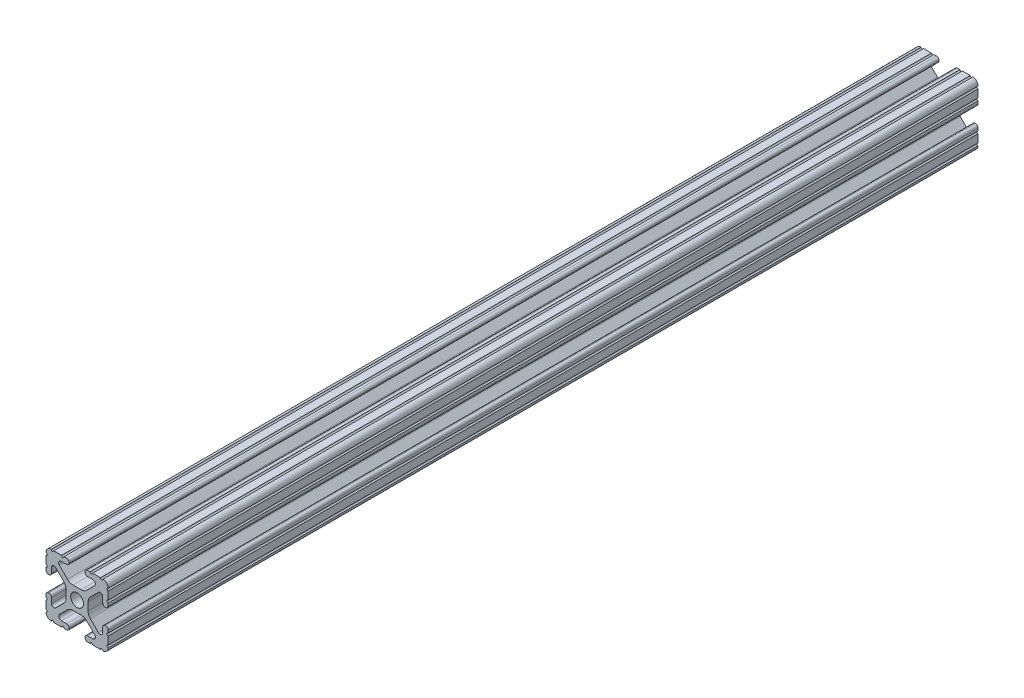
SolidWorks part; units mm, degrees
ref_plane "Front Plane" through (0, 0, 0) normal (0, 0, 1) x (1, 0, 0)
ref_plane "Top Plane" through (0, 0, 0) normal (0, 1, 0) x (1, 0, 0)
ref_plane "Right Plane" through (0, 0, 0) normal (1, 0, 0) x (0, 0, -1)
sketch "Sketch1" plane through (0, 0, 0) normal (0, 0, 1) x (1, 0, 0)
  line L88 (-7.1797, -8.6452) -> (-3.9523, -5.4237)
  line L89 (-1.7093, -4.4958) -> (1.7093, -4.4958)
  line L90 (3.9523, -5.4237) -> (7.1797, -8.6452)
  line L91 (6.4164, -10.4902) -> (4.2875, -10.4902)
  line L92 (3.2385, -11.5392) -> (3.2385, -11.651)
  line L93 (4.2875, -12.7) -> (5.3171, -12.7)
  line L94 (6.3331, -12.7) -> (9.5504, -12.7)
  line L95 (12.7, -9.5504) -> (12.7, -6.3331)
  line L96 (12.7, -5.3171) -> (12.7, -4.2875)
  line L97 (11.651, -3.2385) -> (11.5392, -3.2385)
  line L98 (10.4902, -4.2875) -> (10.4902, -6.4021)
  line L99 (8.7371, -7.1294) -> (5.441, -3.8408)
  line L100 (4.5085, -1.5932) -> (4.5085, 1.5932)
  line L101 (5.441, 3.8408) -> (8.7371, 7.1294)
  line L102 (10.4902, 6.4021) -> (10.4902, 4.2875)
  line L103 (11.5392, 3.2385) -> (11.651, 3.2385)
  line L104 (12.7, 4.2875) -> (12.7, 5.3171)
  line L105 (12.7, 6.3331) -> (12.7, 9.5504)
  line L106 (9.5504, 12.7) -> (6.3331, 12.7)
  line L107 (5.3171, 12.7) -> (4.2875, 12.7)
  line L108 (3.2385, 11.651) -> (3.2385, 11.5392)
  line L109 (4.2875, 10.4902) -> (6.4768, 10.4902)
  line L110 (7.207, 8.7244) -> (3.8983, 5.4232)
  line L111 (1.6558, 4.4958) -> (-1.6558, 4.4958)
  line L112 (-3.8983, 5.4232) -> (-7.207, 8.7244)
  line L113 (-6.4768, 10.4902) -> (-4.2875, 10.4902)
  line L114 (-3.2385, 11.5392) -> (-3.2385, 11.651)
  line L115 (-4.2875, 12.7) -> (-5.3171, 12.7)
  line L116 (-6.3331, 12.7) -> (-9.5504, 12.7)
  line L117 (-12.7, 9.5504) -> (-12.7, 6.3331)
  line L118 (-12.7, 5.3171) -> (-12.7, 4.2875)
  line L119 (-11.651, 3.2385) -> (-11.5392, 3.2385)
  line L120 (-10.4902, 4.2875) -> (-10.4902, 6.4021)
  line L121 (-8.7371, 7.1294) -> (-5.441, 3.8408)
  line L122 (-4.5085, 1.5932) -> (-4.5085, -1.5932)
  line L123 (-5.441, -3.8408) -> (-8.7371, -7.1294)
  line L124 (-10.4902, -6.4021) -> (-10.4902, -4.2875)
  line L125 (-11.5392, -3.2385) -> (-11.651, -3.2385)
  line L126 (-12.7, -4.2875) -> (-12.7, -5.3171)
  line L127 (-12.7, -6.3331) -> (-12.7, -9.5504)
  line L128 (-9.5504, -12.7) -> (-6.3331, -12.7)
  line L129 (-5.3171, -12.7) -> (-4.2875, -12.7)
  line L130 (-3.2385, -11.651) -> (-3.2385, -11.5392)
  line L131 (-4.2875, -10.4902) -> (-6.4164, -10.4902)
  circle A1 centre (0, 0) radius 2.6035
  arc A104 (-7.1797, -8.6452) -> (-6.4164, -10.4902) centre (-6.4164, -9.4098) ccw
  arc A105 (-1.7093, -4.4958) -> (-3.9523, -5.4237) centre (-1.7093, -7.6708) ccw
  arc A106 (3.9523, -5.4237) -> (1.7093, -4.4958) centre (1.7093, -7.6708) ccw
  arc A107 (6.4164, -10.4902) -> (7.1797, -8.6452) centre (6.4164, -9.4098) ccw
  arc A108 (4.2875, -10.4902) -> (3.2385, -11.5392) centre (4.2875, -11.5392) ccw
  arc A109 (3.2385, -11.651) -> (4.2875, -12.7) centre (4.2875, -11.651) ccw
  arc A110 (6.3331, -12.7) -> (5.3171, -12.7) centre (5.8251, -12.7) ccw
  arc A111 (10.5664, -12.6998) -> (9.5504, -12.7) centre (10.0584, -12.7) ccw
  arc A112 (10.5664, -12.6998) -> (12.6998, -10.5664) centre (10.5918, -10.5918) ccw
  arc A113 (12.7, -9.5504) -> (12.6998, -10.5664) centre (12.7, -10.0584) ccw
  arc A114 (12.7, -5.3171) -> (12.7, -6.3331) centre (12.7, -5.8251) ccw
  arc A115 (12.7, -4.2875) -> (11.651, -3.2385) centre (11.651, -4.2875) ccw
  arc A116 (11.5392, -3.2385) -> (10.4902, -4.2875) centre (11.5392, -4.2875) ccw
  arc A117 (8.7371, -7.1294) -> (10.4902, -6.4021) centre (9.4628, -6.4021) ccw
  arc A118 (4.5085, -1.5932) -> (5.441, -3.8408) centre (7.6835, -1.5932) ccw
  arc A119 (5.441, 3.8408) -> (4.5085, 1.5932) centre (7.6835, 1.5932) ccw
  arc A120 (10.4902, 6.4021) -> (8.7371, 7.1294) centre (9.4628, 6.4021) ccw
  arc A121 (10.4902, 4.2875) -> (11.5392, 3.2385) centre (11.5392, 4.2875) ccw
  arc A122 (11.651, 3.2385) -> (12.7, 4.2875) centre (11.651, 4.2875) ccw
  arc A123 (12.7, 6.3331) -> (12.7, 5.3171) centre (12.7, 5.8251) ccw
  arc A124 (12.6998, 10.5664) -> (12.7, 9.5504) centre (12.7, 10.0584) ccw
  arc A125 (12.6998, 10.5664) -> (10.5664, 12.6998) centre (10.5918, 10.5918) ccw
  arc A126 (9.5504, 12.7) -> (10.5664, 12.6998) centre (10.0584, 12.7) ccw
  arc A127 (5.3171, 12.7) -> (6.3331, 12.7) centre (5.8251, 12.7) ccw
  arc A128 (4.2875, 12.7) -> (3.2385, 11.651) centre (4.2875, 11.651) ccw
  arc A129 (3.2385, 11.5392) -> (4.2875, 10.4902) centre (4.2875, 11.5392) ccw
  arc A130 (7.207, 8.7244) -> (6.4768, 10.4902) centre (6.4768, 9.4563) ccw
  arc A131 (1.6558, 4.4958) -> (3.8983, 5.4232) centre (1.6558, 7.6708) ccw
  arc A132 (-3.8983, 5.4232) -> (-1.6558, 4.4958) centre (-1.6558, 7.6708) ccw
  arc A133 (-6.4768, 10.4902) -> (-7.207, 8.7244) centre (-6.4768, 9.4563) ccw
  arc A134 (-4.2875, 10.4902) -> (-3.2385, 11.5392) centre (-4.2875, 11.5392) ccw
  arc A135 (-3.2385, 11.651) -> (-4.2875, 12.7) centre (-4.2875, 11.651) ccw
  arc A136 (-6.3331, 12.7) -> (-5.3171, 12.7) centre (-5.8251, 12.7) ccw
  arc A137 (-10.5664, 12.6998) -> (-9.5504, 12.7) centre (-10.0584, 12.7) ccw
  arc A138 (-10.5664, 12.6998) -> (-12.6998, 10.5664) centre (-10.5918, 10.5918) ccw
  arc A139 (-12.7, 9.5504) -> (-12.6998, 10.5664) centre (-12.7, 10.0584) ccw
  arc A140 (-12.7, 5.3171) -> (-12.7, 6.3331) centre (-12.7, 5.8251) ccw
  arc A141 (-12.7, 4.2875) -> (-11.651, 3.2385) centre (-11.651, 4.2875) ccw
  arc A142 (-11.5392, 3.2385) -> (-10.4902, 4.2875) centre (-11.5392, 4.2875) ccw
  arc A143 (-8.7371, 7.1294) -> (-10.4902, 6.4021) centre (-9.4628, 6.4021) ccw
  arc A144 (-4.5085, 1.5932) -> (-5.441, 3.8408) centre (-7.6835, 1.5932) ccw
  arc A145 (-5.441, -3.8408) -> (-4.5085, -1.5932) centre (-7.6835, -1.5932) ccw
  arc A146 (-10.4902, -6.4021) -> (-8.7371, -7.1294) centre (-9.4628, -6.4021) ccw
  arc A147 (-10.4902, -4.2875) -> (-11.5392, -3.2385) centre (-11.5392, -4.2875) ccw
  arc A148 (-11.651, -3.2385) -> (-12.7, -4.2875) centre (-11.651, -4.2875) ccw
  arc A149 (-12.7, -6.3331) -> (-12.7, -5.3171) centre (-12.7, -5.8251) ccw
  arc A150 (-12.6998, -10.5664) -> (-12.7, -9.5504) centre (-12.7, -10.0584) ccw
  arc A151 (-12.6998, -10.5664) -> (-10.5664, -12.6998) centre (-10.5918, -10.5918) ccw
  arc A152 (-9.5504, -12.7) -> (-10.5664, -12.6998) centre (-10.0584, -12.7) ccw
  arc A153 (-5.3171, -12.7) -> (-6.3331, -12.7) centre (-5.8251, -12.7) ccw
  arc A154 (-4.2875, -12.7) -> (-3.2385, -11.651) centre (-4.2875, -11.651) ccw
  arc A155 (-3.2385, -11.5392) -> (-4.2875, -10.4902) centre (-4.2875, -11.5392) ccw
extrude "Boss-Extrude1" add sketch "Sketch1" along normal mid plane 355.6
ref_plane "Plane1" through (0, 0, 0) normal (0, 1, 0) x (1, 0, 0)
ref_plane "Plane2" through (0, 0, 0) normal (-1, 0, 0) x (0, 0, 1)
